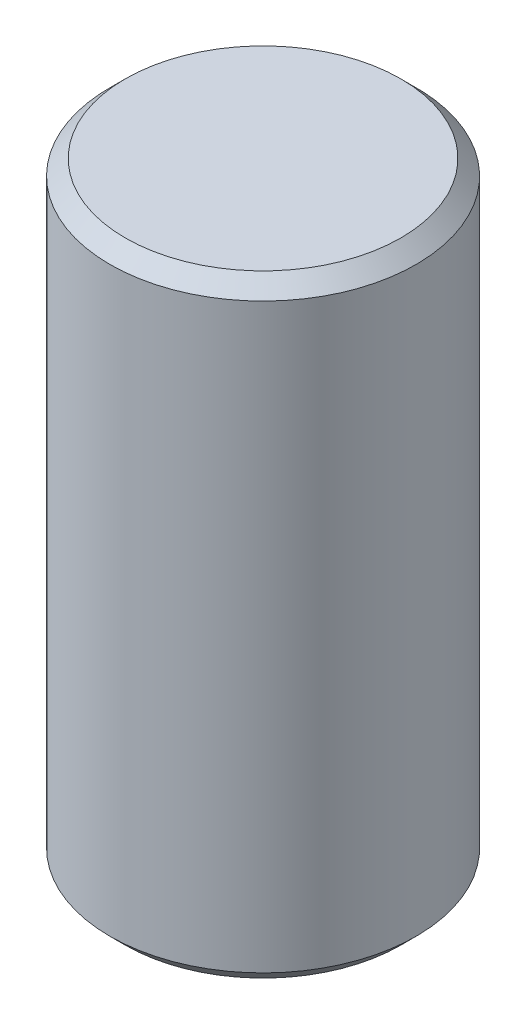
SolidWorks part; units mm, degrees
ref_plane "Front" through (0, 0, 0) normal (0, 0, 1) x (1, 0, 0)
ref_plane "Top" through (0, 0, 0) normal (0, 1, 0) x (1, 0, 0)
ref_plane "Right" through (0, 0, 0) normal (1, 0, 0) x (0, 0, -1)
sketch "Sketch1" plane through (0, 0, 0) normal (0, 1, 0) x (1, 0, 0)
  circle A0 centre (0, 0) radius 1
  dimension "D1" = 2
extrude "Boss-Extrude1" add sketch "Sketch1" along normal blind 4
chamfer "Chamfer1" distance 0.1 angle 45 2 edges at (0, 4, 1) (0, 0, 1)
